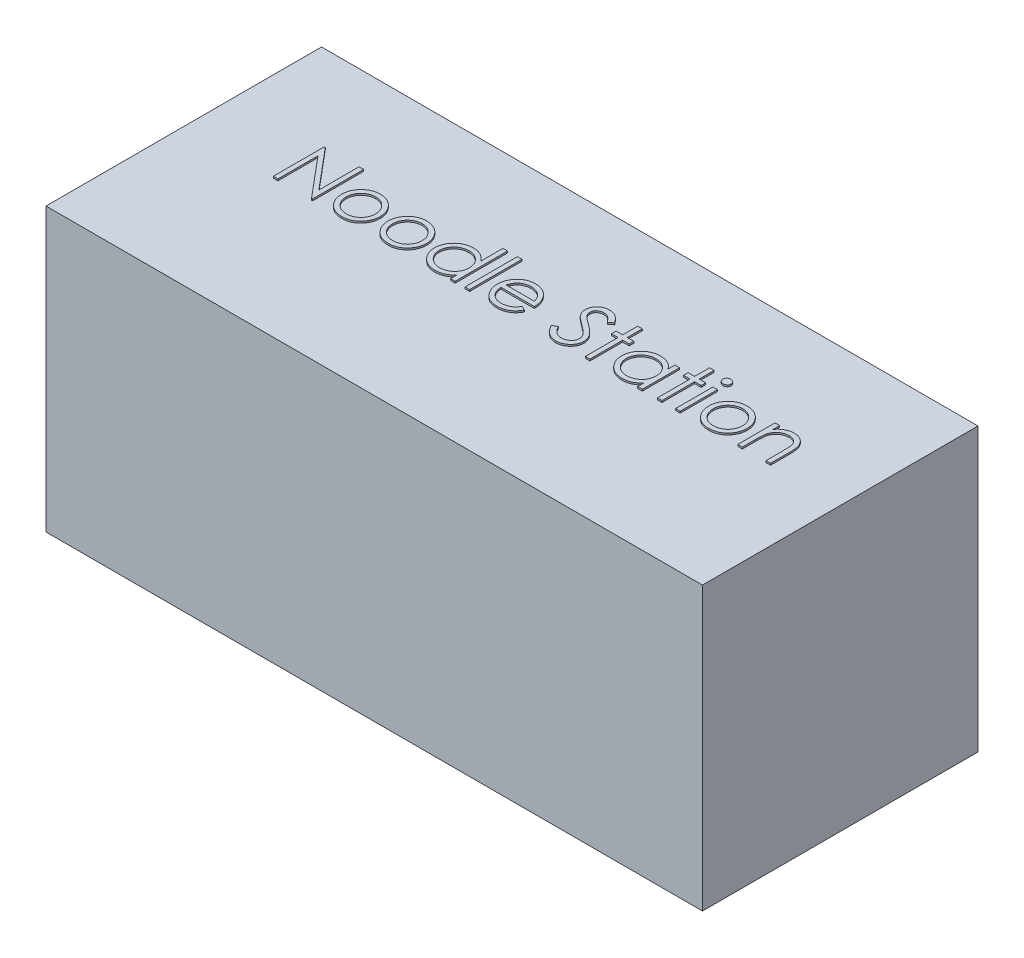
SolidWorks part; units mm, degrees
ref_plane "Front Plane" through (0, 0, 0) normal (0, 0, 1) x (1, 0, 0)
ref_plane "Top Plane" through (0, 0, 0) normal (0, 1, 0) x (1, 0, 0)
ref_plane "Right Plane" through (0, 0, 0) normal (1, 0, 0) x (0, 0, -1)
sketch "Sketch1" plane through (0, 0, 0) normal (0, 1, 0) x (1, 0, 0)
  line L1 (-965, -405) -> (965, -405)
  line L2 (-965, -405) -> (-965, 405)
  line L3 (-965, 405) -> (965, 405)
  line L4 (965, -405) -> (965, 405)
  line L5 (-965, -405) -> (965, 405) construction
  line L6 (-965, 405) -> (965, -405) construction
  point P0 (0, 0)
  dimension "D1" = 1930
  dimension "D2" = 810
extrude "Boss-Extrude1" add sketch "Sketch1" along normal blind 830
sketch "Sketch2" plane through (0, 830, 0) normal (0, 1, 0) x (1, 0, 0)
  line L0 (-965, 405) -> (-965, -405) construction
  line L1 (-965, 0) -> (965, 0) construction
  line L2 (965, -405) -> (965, 405) construction
  text T0 "Noodle Station" font "Century Gothic" height 150
  point P9 (-744.8839, 0)
  point P10 (-670.6093, 0)
  point P11 (-720.8539, 0)
extrude "Boss-Extrude2" add sketch "Sketch2" along normal blind 5
